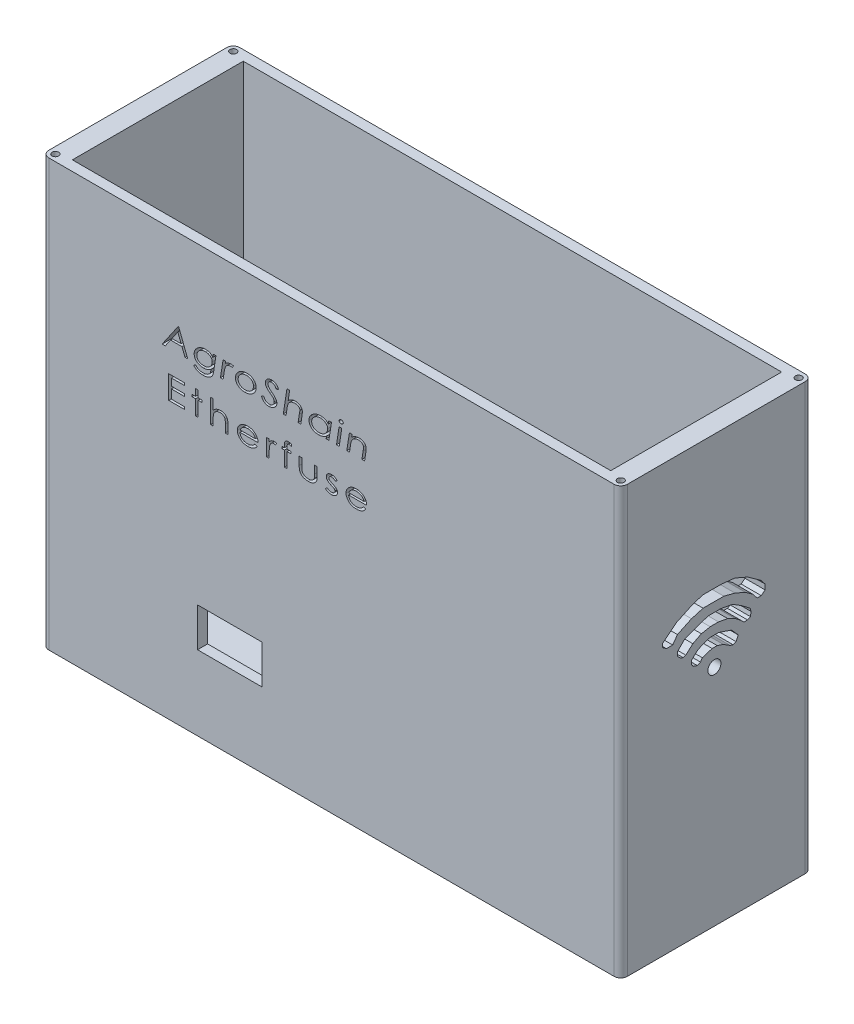
SolidWorks part; units mm, degrees
other "Marca1"
sketch "Croquis10" plane through (-3.0444, 0, 27.43) normal (0, 0, 1) x (1, 0, 0)
ref_plane "Alzado" through (0, 0, 0) normal (0, 0, 1) x (1, 0, 0)
ref_plane "Planta" through (0, 0, 0) normal (0, 1, 0) x (1, 0, 0)
ref_plane "Vista lateral" through (0, 0, 0) normal (1, 0, 0) x (0, 0, -1)
sketch "Croquis1" plane through (0, 0, 0) normal (0, 1, 0) x (1, 0, 0)
  line L1 (0, 0) -> (81.6, 0)
  line L2 (0, 0) -> (0, -25.9)
  line L3 (0, -25.9) -> (81.6, -25.9)
  line L4 (81.6, 0) -> (81.6, -25.9)
  line L5 (-3.0444, 1.53) -> (84.6444, 1.53)
  line L6 (-3.0444, 1.53) -> (-3.0444, -27.43)
  line L7 (-3.0444, -27.43) -> (84.6444, -27.43)
  line L8 (84.6444, 1.53) -> (84.6444, -27.43)
  line L9 (-3.0444, 1.53) -> (84.6444, -27.43) construction
  line L10 (-3.0444, -27.43) -> (84.6444, 1.53) construction
  point P5 (40.8, -12.95)
  dimension "D1" = 81.6
  dimension "D2" = 25.9
  dimension "D3" = 87.6888
  dimension "D4" = 28.96
  dimension "D5" = 1.53
  dimension "D6" = 1.53
  dimension "D7" = 3.0444
  dimension "D8" = 3.0444
extrude "Saliente-Extruir1" add sketch "Croquis1" along normal blind 72.4
sketch "Croquis2" plane through (0, 0, 0) normal (0, 1, 0) x (1, 0, 0)
  line L0 (81.6, 0) -> (0, 0) construction
  line L1 (0, -33.9) -> (81.6, -33.9)
  line L2 (0, -33.9) -> (0, 0)
  line L3 (0, 0) -> (81.6, 0)
  line L4 (81.6, -33.9) -> (81.6, 0)
  line L5 (0, -33.9) -> (81.6, 0) construction
  line L6 (0, 0) -> (81.6, -33.9) construction
  line L7 (81.6, -25.9) -> (81.6, 0) construction
  point P0 (40.8, -16.95)
extrude "Saliente-Extruir2" add sketch "Croquis2" along normal blind 2.4
sketch "Croquis3" plane through (0, 2.4, 0) normal (0, 1, 0) x (1, 0, 0)
  line L0 (0, 0) -> (33.4, 0)
  line L1 (81.6, 0) -> (0, 0) construction
  line L2 (33.4, 0) -> (33.4, -2.5)
  line L3 (33.4, -2.5) -> (0, -2.5)
  line L4 (0, 0) -> (0, -25.9) construction
  line L5 (0, -2.5) -> (0, 0)
  line L6 (0, -25.9) -> (33.4, -25.9)
  line L7 (0, -25.9) -> (81.6, -25.9) construction
  line L8 (33.4, -25.9) -> (33.4, -23.4)
  line L9 (33.4, -23.4) -> (0, -23.4)
  line L10 (0, 0) -> (0, -25.9) construction
  line L11 (0, -23.4) -> (0, -25.9)
  dimension "D1" = 33.4
  dimension "D2" = 2.5
  dimension "D3" = 2.5
  dimension "D4" = 33.4
extrude "Cortar-Extruir4" cut sketch "Croquis3" against normal through all
sketch "Croquis4" plane through (84.6444, 0, 0) normal (1, 0, 0) x (0, 0, -1)
  line L0 (-12.95, 0) -> (-12.95, 12.7) construction
  line L1 (-27.43, 0) -> (1.53, 0) construction
  line L2 (-27.43, 12.7) -> (-24.86, 12.7) construction
  line L3 (-27.43, 72.4) -> (-27.43, 0) construction
  line L4 (-25.9, 0) -> (-25.9, 6.1) construction
  line L5 (1.53, 12.7) -> (-1.04, 12.7) construction
  line L6 (1.53, 72.4) -> (1.53, 0) construction
  line L8 (-25.9, 6.1) -> (-1.04, 6.1)
  line L9 (-25.9, 6.1) -> (-25.9, 12.7)
  line L10 (-25.9, 12.7) -> (-1.04, 12.7)
  line L11 (-1.04, 6.1) -> (-1.04, 12.7)
  dimension "D1" = 12.7
  dimension "D2" = 2.57
  dimension "D3" = 6.1
  dimension "D4" = 2.57
  dimension "D5" = 24.86
  dimension "D6" = 6.6
sketch "Croquis8" plane through (0, 2.4, 0) normal (0, 1, 0) x (1, 0, 0)
  line L1 (0, -27.43) -> (81.6, -27.43)
  line L2 (0, -27.43) -> (0, -33.9)
  line L3 (0, -33.9) -> (81.6, -33.9)
  line L4 (81.6, -27.43) -> (81.6, -33.9)
extrude "Cortar-Extruir10" cut sketch "Croquis8" against normal blind 10
sketch "Croquis14" plane through (0, 0, 0) normal (0, 0, 1) x (1, 0, 0)
  line L0 (0, 0) -> (44.1534, 0) construction
  line L1 (44.1534, 0) -> (44.1534, 2.4)
  line L2 (81.6, 2.4) -> (33.4, 2.4) construction
  line L3 (44.1534, 2.4) -> (44.1534, 64.6) construction
  line L5 (84.7267, 64.6) -> (-3.3035, 64.6)
  line L6 (84.7267, 64.6) -> (84.7267, 72.6338)
  line L7 (84.7267, 72.6338) -> (-3.3035, 72.6338)
  line L8 (-3.3035, 64.6) -> (-3.3035, 72.6338)
  dimension "D1" = 62.2
extrude "Cortar-Extruir13" cut sketch "Croquis14" against normal through all both and the other way through all contours L6 L5 L8 L7
sketch "Croquis15" plane through (0, 0, 25.9) normal (0, 0, -1) x (-1, 0, 0)
  line L0 (0, 0) -> (-20.5, 0) construction
  line L1 (0, 0) -> (-33.4, 0) construction
  line L2 (-20.5, 0) -> (-30.3, 0) construction
  line L3 (-30.3, 0) -> (-30.3, 17.2) construction
  line L9 (-30.3, 17.2) -> (-20.5, 17.2)
  line L10 (-30.3, 17.2) -> (-30.3, 11.3097)
  line L11 (-30.3, 11.3097) -> (-20.5, 11.3097)
  line L12 (-20.5, 17.2) -> (-20.5, 11.3097)
  dimension "D1" = 20.5
  dimension "D2" = 9.8
  dimension "D3" = 17.2
extrude "Cortar-Extruir18" cut sketch "Croquis15" against normal blind 10 contours L10 L9 L12 L11
fillet "Redondeo1" radius 1 4 edges at (-3.0444, 32.3, -1.53) (-3.0444, 32.3, 27.43) (84.6444, 32.3, -1.53) (84.6444, 32.3, 27.43)
sketch "Croquis17" plane through (0, 64.6, 0) normal (0, 1, 0) x (1, 0, 0)
  circle A0 centre (-2.0444, -26.43) radius 0.5
  circle A1 centre (-2.0444, 0.53) radius 0.5
  circle A2 centre (83.6444, -26.43) radius 0.5
  circle A3 centre (83.6444, 0.53) radius 0.5
  dimension "D1" = 1
  dimension "D2" = 1
  dimension "D3" = 1
  dimension "D4" = 1
  dimension "D5" = 26.96
  dimension "D6" = 26.96
  dimension "D7" = 85.6888
  dimension "D8" = 85.6888
extrude "Cortar-Extruir19" cut sketch "Croquis17" against normal blind 10
sketch "Croquis18" plane through (84.6444, 0, 0) normal (1, 0, 0) x (0, 0, -1)
  line L0 (49.6777, 150.281) -> (349.6777, 150.281) construction
  line L1 (-21.0653, 41.0776) -> (-19.0373, 42.7001)
  line L2 (-19.0373, 42.7001) -> (-16.4561, 43.9169)
  line L3 (-16.4561, 43.9169) -> (-14.9443, 44.3594)
  line L4 (-14.9443, 44.3594) -> (-13.5062, 44.3594)
  line L5 (-13.5062, 44.3594) -> (-12.0681, 44.3594)
  line L6 (-12.0681, 44.3594) -> (-10.1138, 44.1381)
  line L7 (-10.1138, 44.1381) -> (-8.1964, 43.3085)
  line L8 (-8.1964, 43.3085) -> (-6.2052, 41.8888)
  line L9 (-6.2052, 41.8888) -> (-5.5563, 41.0776)
  line L10 (-5.5563, 41.0776) -> (-5.5563, 40.3033)
  line L11 (-5.5563, 40.3033) -> (-6.1363, 39.8392)
  line L12 (-6.1363, 39.8392) -> (-6.7583, 39.8392)
  line L13 (-6.7583, 39.8392) -> (-7.4393, 40.6905)
  line L14 (-7.4393, 40.6905) -> (-8.5513, 41.4832)
  line L15 (-8.5513, 41.4832) -> (-10.1138, 42.1593)
  line L16 (-10.1138, 42.1593) -> (-11.81, 42.5987)
  line L17 (-11.81, 42.5987) -> (-13.1006, 42.5987)
  line L18 (-13.1006, 42.5987) -> (-14.9443, 42.5987)
  line L19 (-14.9443, 42.5987) -> (-16.7021, 42.0842)
  line L20 (-16.7021, 42.0842) -> (-18.8372, 41.0776)
  line L21 (-18.8372, 41.0776) -> (-19.5567, 40.0686)
  line L22 (-19.5567, 40.0686) -> (-20.5122, 40.0686)
  line L23 (-20.5122, 40.0686) -> (-21.0653, 40.4629)
  line L24 (-21.0653, 40.4629) -> (-21.0653, 41.0776)
  line L25 (-15.3466, 35.7205) -> (-15.8079, 35.4898)
  line L26 (-15.8079, 35.4898) -> (-16.3655, 35.6757)
  line L27 (-16.3655, 35.6757) -> (-16.7021, 36.0041)
  line L28 (-16.7021, 36.0041) -> (-16.7021, 36.6159)
  line L29 (-16.7021, 36.6159) -> (-16.2925, 37.0358)
  line L30 (-16.2925, 37.0358) -> (-15.8079, 37.4707)
  line L31 (-15.8079, 37.4707) -> (-14.9443, 37.9025)
  line L32 (-14.9443, 37.9025) -> (-14.2258, 38.122)
  line L33 (-14.2258, 38.122) -> (-13.8737, 38.2296)
  line L34 (-13.8737, 38.2296) -> (-12.6058, 38.2296)
  line L35 (-12.6058, 38.2296) -> (-11.6374, 37.9067)
  line L36 (-11.6374, 37.9067) -> (-10.6564, 37.5797)
  line L37 (-10.6564, 37.5797) -> (-10.1138, 36.9752)
  line L38 (-10.1138, 36.9752) -> (-9.6181, 36.4229)
  line L39 (-9.6181, 36.4229) -> (-9.9601, 35.7205)
  line L40 (-9.9601, 35.7205) -> (-10.3851, 35.5079)
  line L41 (-10.3851, 35.5079) -> (-10.8519, 35.6635)
  line L42 (-10.8519, 35.6635) -> (-11.5068, 36.0717)
  line L43 (-11.5068, 36.0717) -> (-11.8893, 36.31)
  line L44 (-11.8893, 36.31) -> (-12.6058, 36.5489)
  line L45 (-12.6058, 36.5489) -> (-12.807, 36.6159)
  line L46 (-12.807, 36.6159) -> (-13.5733, 36.6159)
  line L47 (-13.5733, 36.6159) -> (-14.4678, 36.3427)
  line L48 (-14.4678, 36.3427) -> (-15.0684, 36.1592)
  line L49 (-15.0684, 36.1592) -> (-15.3466, 35.7205)
  line L50 (-17.5667, 37.7432) -> (-17.9706, 37.6198)
  line L51 (-17.9706, 37.6198) -> (-18.3622, 37.7504)
  line L52 (-18.3622, 37.7504) -> (-18.8372, 38.2139)
  line L53 (-18.8372, 38.2139) -> (-18.8372, 38.8206)
  line L54 (-18.8372, 38.8206) -> (-17.7686, 39.9158)
  line L55 (-17.7686, 39.9158) -> (-16.2925, 40.4629)
  line L56 (-16.2925, 40.4629) -> (-15.2075, 40.8651)
  line L57 (-15.2075, 40.8651) -> (-14.1302, 41.1942)
  line L58 (-14.1302, 41.1942) -> (-12.2476, 41.1942)
  line L59 (-12.2476, 41.1942) -> (-10.4813, 40.8651)
  line L60 (-10.4813, 40.8651) -> (-9.0683, 39.9845)
  line L61 (-9.0683, 39.9845) -> (-7.8221, 39.032)
  line L62 (-7.8221, 39.032) -> (-7.6648, 38.5172)
  line L63 (-7.6648, 38.5172) -> (-7.7786, 37.9067)
  line L64 (-7.7786, 37.9067) -> (-8.2111, 37.6857)
  line L65 (-8.2111, 37.6857) -> (-8.7667, 37.6857)
  line L66 (-8.7667, 37.6857) -> (-9.3061, 38.212)
  line L67 (-9.3061, 38.212) -> (-10.1138, 38.8294)
  line L68 (-10.1138, 38.8294) -> (-11.2207, 39.3682)
  line L69 (-11.2207, 39.3682) -> (-12.6058, 39.6262)
  line L70 (-12.6058, 39.6262) -> (-13.8737, 39.6262)
  line L71 (-13.8737, 39.6262) -> (-15.2075, 39.3682)
  line L72 (-15.2075, 39.3682) -> (-16.4973, 38.7089)
  line L73 (-16.4973, 38.7089) -> (-17.5667, 37.7432)
  circle A0 centre (-13.2353, 34.0054) radius 0.9905
extrude "Cortar-Extruir20" cut sketch "Croquis18" against normal blind 10
sketch "Croquis20" plane through (0, 0, 27.43) normal (0, 0, 1) x (1, 0, 0)
  line L0 (10.4306, 48.7501) -> (51.3449, 48.7501) construction
  line L1 (10.4306, 41.8607) -> (51.6261, 41.8607) construction
  text T0 "<i>AgroShain</i>" font "Century Gothic" height 3.5
  text T1 "Etherfuse" font "Century Gothic" height 3.5
extrude "Cortar-Extruir21" cut sketch "Croquis20" against normal blind 10
